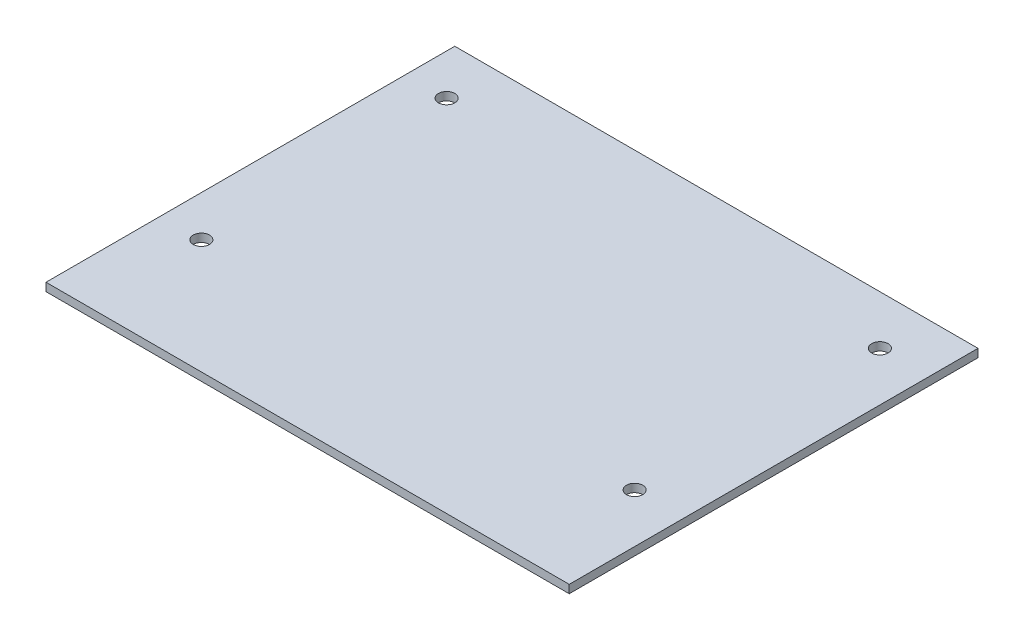
SolidWorks part; units mm, degrees
ref_plane "Front Plane" through (0, 0, 0) normal (0, 0, 1) x (1, 0, 0)
ref_plane "Top Plane" through (0, 0, 0) normal (0, 1, 0) x (1, 0, 0)
ref_plane "Right Plane" through (0, 0, 0) normal (1, 0, 0) x (0, 0, -1)
sketch "Sketch1" plane through (0, 0, 0) normal (0, 1, 0) x (1, 0, 0)
  line L1 (-203.2, 158.75) -> (203.2, 158.75)
  line L2 (-203.2, 158.75) -> (-203.2, -158.75)
  line L3 (-203.2, -158.75) -> (203.2, -158.75)
  line L4 (203.2, 158.75) -> (203.2, -158.75)
  line L5 (-203.2, 158.75) -> (203.2, -158.75) construction
  line L6 (-203.2, -158.75) -> (203.2, 158.75) construction
  point P0 (0, 0)
  dimension "D1" = 406.4
  dimension "D2" = 317.5
extrude "Boss-Extrude1" add sketch "Sketch1" along normal blind 6.35
hole_wizard "1/2 (0.5) Diameter Hole1" positions "Sketch4" profile "Sketch5" hole size "1/2" standard "ANSI Inch"
sketch "Sketch4" plane through (0, 6.35, 0) normal (0, 1, 0) x (1, 0, 0)
  line L0 (203.2, -158.75) -> (203.2, 158.75) construction
  line L1 (203.2, 158.75) -> (-203.2, 158.75) construction
  point P0 (-171.45, 120.65)
  point P2 (165.1, 120.65)
  point P4 (165.1, -69.85)
  point P6 (-171.45, -69.85)
  point P11 (0, 0)
  point P14 (0, 0)
  point P17 (0, 0)
  point P18 (0, 0)
  point P19 (0, 0)
  point P20 (0, 0)
  point P21 (0, 0)
  point P22 (0, 0)
  point P23 (0, 0)
  dimension "D1" = 336.55
  dimension "D2" = 38.1
  dimension "D3" = 38.1
  dimension "D4" = 190.5
sketch "Sketch5" plane through (-171.45, 6.35, -120.65) normal (1, 0, 0) x (0, 0, 1)
  line L0 (0, 0) -> (0, 16.5155)
  line L1 (0, 16.5155) -> (6.35, 12.7)
  line L2 (6.35, 12.7) -> (6.35, 0)
  line L5 (6.35, 0) -> (0, 0)
  line L10 (0, 16.5155) -> (-6.35, 12.7) construction
  line L11 (0, -6.35) -> (0, 107.95) construction
  dimension "Hole Dia." = 12.7
  dimension "Hole Depth" = 12.7
  dimension "Drill Angle" = 118
